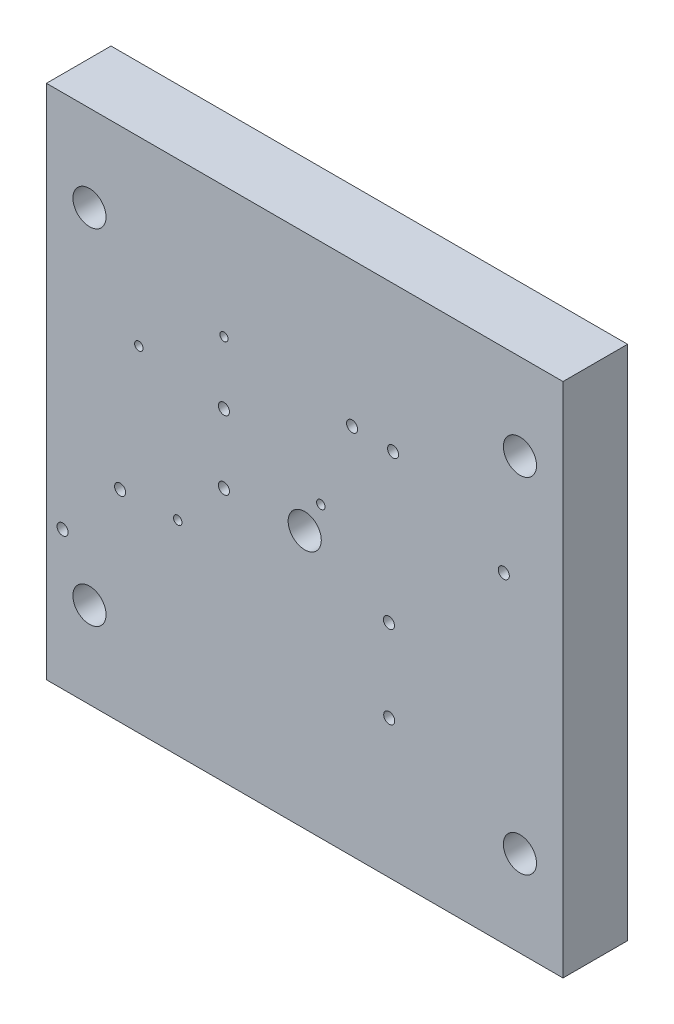
SolidWorks part; units mm, degrees
ref_plane "Front Plane" through (0, 0, 0) normal (0, 0, 1) x (1, 0, 0)
ref_plane "Top Plane" through (0, 0, 0) normal (0, 1, 0) x (1, 0, 0)
ref_plane "Right Plane" through (0, 0, 0) normal (1, 0, 0) x (0, 0, -1)
sketch "Sketch1" plane through (0, 0, 0) normal (0, 0, 1) x (1, 0, 0)
  line L1 (-152.4, 152.4) -> (152.4, 152.4)
  line L2 (-152.4, 152.4) -> (-152.4, -152.4)
  line L3 (-152.4, -152.4) -> (152.4, -152.4)
  line L4 (152.4, 152.4) -> (152.4, -152.4)
  line L5 (-152.4, 152.4) -> (152.4, -152.4) construction
  line L6 (-152.4, -152.4) -> (152.4, 152.4) construction
  point P0 (0, 0)
  dimension "D1" = 304.8
  dimension "D2" = 304.8
extrude "Boss-Extrude1" add sketch "Sketch1" along normal blind 38.1
sketch "Sketch2" plane through (0, 0, 38.1) normal (0, 0, 1) x (1, 0, 0)
  line L0 (-152.4, 0) -> (152.4, 0) construction
  line L5 (-152.4, 152.4) -> (-152.4, -152.4) construction
  line L6 (152.4, -152.4) -> (152.4, 152.4) construction
  line L7 (-152.4, -101.6) -> (152.4, -101.6) construction
  line L8 (-152.4, 101.6) -> (152.4, 101.6) construction
  line L9 (0, 101.6) -> (0, -101.6) construction
  line L10 (127, 101.6) -> (127, -101.6) construction
  line L11 (-127, 101.6) -> (-127, -101.6) construction
  circle A0 centre (-127, 101.6) radius 6.5151
  circle A1 centre (127, 101.6) radius 6.5151
  circle A2 centre (127, -101.6) radius 6.5151
  circle A3 centre (-127, -101.6) radius 6.5151
  circle A4 centre (0, 0) radius 6.5151
  dimension "D5" = 13.0302
  dimension "D1" = 101.6
  dimension "D2" = 101.6
  dimension "D3" = 127
  dimension "D4" = 127
extrude "HAAS T-Slot Holes" cut sketch "Sketch2" against normal through all
sketch "Sketch3" plane through (0, 0, 38.1) normal (0, 0, 1) x (1, 0, 0)
  circle A0 centre (-127, 101.6) radius 9.779
  circle A1 centre (127, 101.6) radius 9.779
  circle A2 centre (0, 0) radius 9.779
  circle A3 centre (127, -101.6) radius 9.779
  circle A4 centre (-127, -101.6) radius 9.779
  dimension "D1" = 19.558
extrude "HAAS Counter Bores" cut sketch "Sketch3" against normal offset from surface (22.225 mm away) 15.875 contours A0 | A1 | A2 | A3 | A4 up to face at (6.5151, 0, 0)
sketch "Sketch4" plane through (0, 0, 38.1) normal (0, 0, 1) x (1, 0, 0)
  circle A1 centre (49.6872, -22.1117) radius 3.2639
  circle A2 centre (49.6872, -22.1117) radius 3.2639
  circle A5 centre (-108.9203, -33.3883) radius 3.2639
  circle A6 centre (-108.9203, -33.3883) radius 3.2639
  circle A7 centre (-47.6363, -2.1715) radius 3.2639
  circle A8 centre (-47.6363, -2.1715) radius 3.2639
  circle A9 centre (-47.6363, 38.4685) radius 3.2639
  circle A10 centre (-47.6363, 38.4685) radius 3.2639
  circle A11 centre (117.4637, 37.1985) radius 3.2639
  circle A12 centre (117.4637, 37.1985) radius 3.2639
  circle A16 centre (-142.8863, -70.7515) radius 3.2639
  circle A17 centre (49.8631, -70.7515) radius 3.2639
  circle A18 centre (27.9508, 67.3067) radius 3.2639
  circle A19 centre (52.1346, 66.4717) radius 3.2639
  dimension "D1" = 0
  dimension "D3" = 0
  dimension "D4" = 0
  dimension "D5" = 0
  dimension "D6" = 0
extrude "Cut-Extrude1" cut sketch "Sketch4" against normal blind 19.05
sketch "Sketch5" plane through (0, 0, 38.1) normal (0, 0, 1) x (1, 0, 0)
  circle A0 centre (-47.6363, 75.2985) radius 2.4146
  circle A1 centre (-97.8607, 45.4181) radius 2.5
  circle A2 centre (-74.906, -32.0759) radius 2.5
  circle A3 centre (9.5137, 18.1485) radius 2.5
extrude "Cut-Extrude2" cut sketch "Sketch5" against normal blind 12.7
